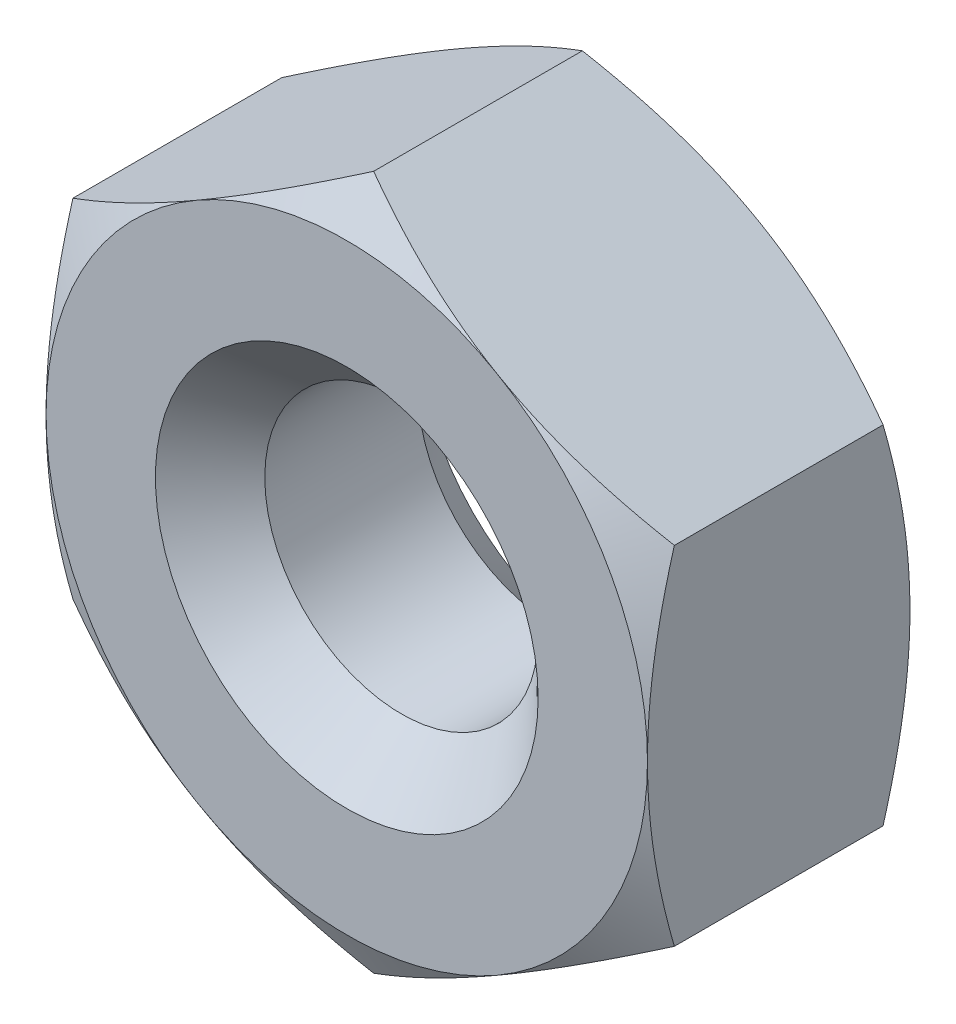
SolidWorks part; units mm, degrees
ref_plane "Спереди" through (0, 0, 0) normal (0, 0, 1) x (1, 0, 0)
ref_plane "Сверху" through (0, 0, 0) normal (0, 1, 0) x (1, 0, 0)
ref_plane "Справа" through (0, 0, 0) normal (1, 0, 0) x (0, 0, -1)
sketch "Эскиз1" plane through (0, 0, 0) normal (0, 0, 1) x (1, 0, 0)
  line L0 (0, 0) -> (2.75, 0) construction
  line L1 (2.75, 1.5877) -> (0, 3.1754)
  line L2 (0, 3.1754) -> (-2.75, 1.5877)
  line L3 (-2.75, 1.5877) -> (-2.75, -1.5877)
  line L4 (-2.75, -1.5877) -> (0, -3.1754)
  line L5 (0, -3.1754) -> (2.75, -1.5877)
  line L6 (2.75, -1.5877) -> (2.75, 1.5877)
  circle A0 centre (0, 0) radius 2.75 construction
  dimension "D1" = 5.5
extrude "Бобышка-Вытянуть1" add sketch "Эскиз1" along normal blind 2.4
hole_wizard "Отверстие обработанное метчиком M31" positions "Эскиз2" profile "Эскиз3" tap size "M3" standard "ISO" end condition up to next
sketch "Эскиз2" plane through (0, 0, 2.4) normal (0, 0, 1) x (1, 0, 0)
  point P0 (0, 0)
sketch "Эскиз3" plane through (0, 0, 2.4) normal (1, 0, 0) x (0, -1, 0)
  line L0 (0, 0) -> (0, 2.4)
  line L1 (0, 2.4) -> (1.25, 2.4)
  line L2 (1.25, 2.4) -> (1.25, 0)
  line L5 (1.25, 0) -> (0, 0)
  line L11 (0, -6.35) -> (0, 107.95) construction
  dimension "Диаметр проходного сверла" = 2.5
  dimension "Глубина проходного сверла" = 2.4
cosmetic thread "Отверстие резьбы1" parameters "D2"=3
chamfer "Фаска1" distance 0.5 angle 45 2 edges at (1.25, 0, 0) (1.25, 0, 2.4)
sketch "Эскиз4" plane through (0, 0, 0) normal (1, 0, 0) x (0, 0, -1)
  line L0 (0, 2.75) -> (0, 4)
  line L1 (0, 1.5877) -> (0, 3.1754) construction
  line L2 (0, 4) -> (-0.7217, 4)
  line L3 (-0.7217, 4) -> (0, 2.75)
  line L4 (-2.4, 2.75) -> (-2.4, 4)
  line L5 (-2.4, 1.5877) -> (-2.4, 3.1754) construction
  line L6 (-2.4, 4) -> (-1.6783, 4)
  line L7 (-1.6783, 4) -> (-2.4, 2.75)
  line L8 (0, 0) -> (-2.4, 0) construction
  line L9 (-2.4, -1.5877) -> (-2.4, 1.5877) construction
  dimension "D1" = 5.5
  dimension "D2" = 8
  dimension "D3" = 30
revolve "Вырез-Повернуть1" cut sketch "Эскиз4" angle 360 about L8
